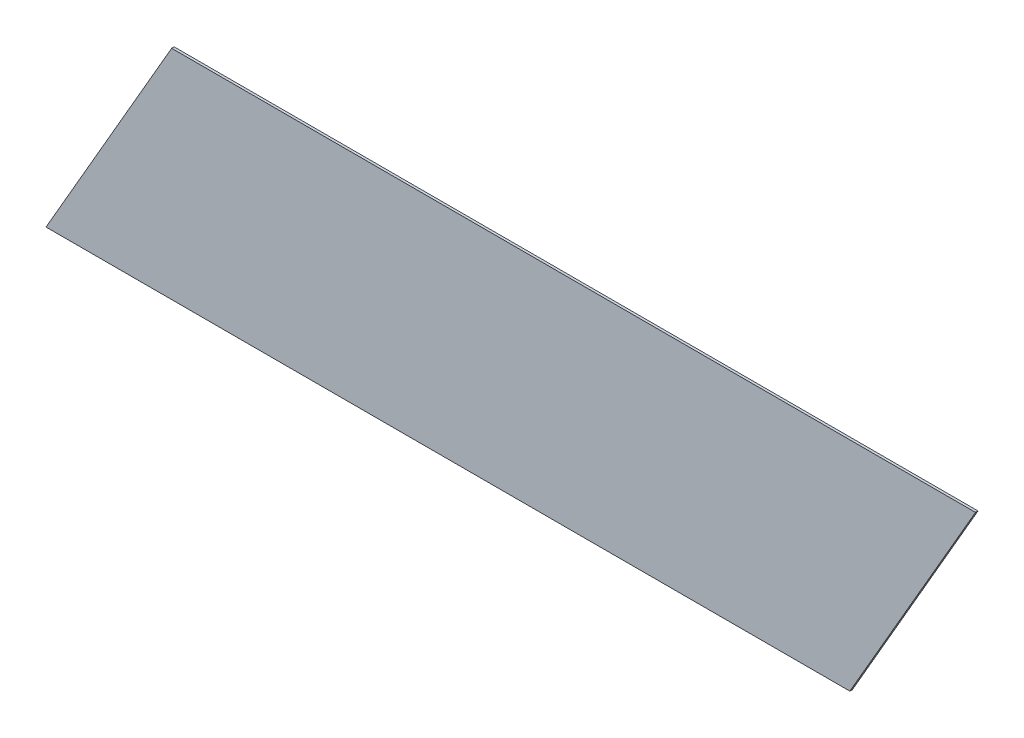
SolidWorks part; units mm, degrees
ref_plane "Front Plane" through (0, 0, 0) normal (0, 0, 1) x (1, 0, 0)
ref_plane "Top Plane" through (0, 0, 0) normal (0, 1, 0) x (1, 0, 0)
ref_plane "Right Plane" through (0, 0, 0) normal (1, 0, 0) x (0, 0, -1)
sketch "Sketch1" plane through (0, 0, 0) normal (0, 0, 1) x (1, 0, 0)
  line L0 (0, 0) -> (10.1614, 17.6)
  line L1 (10.1614, 17.6) -> (75.1614, 17.6)
  line L2 (75.1614, 17.6) -> (65, 0)
  line L3 (65, 0) -> (0, 0)
  dimension "D1" = 17.6
  dimension "D2" = 60
  dimension "D3" = 65
extrude "Boss-Extrude1" add sketch "Sketch1" along normal blind 0.2
